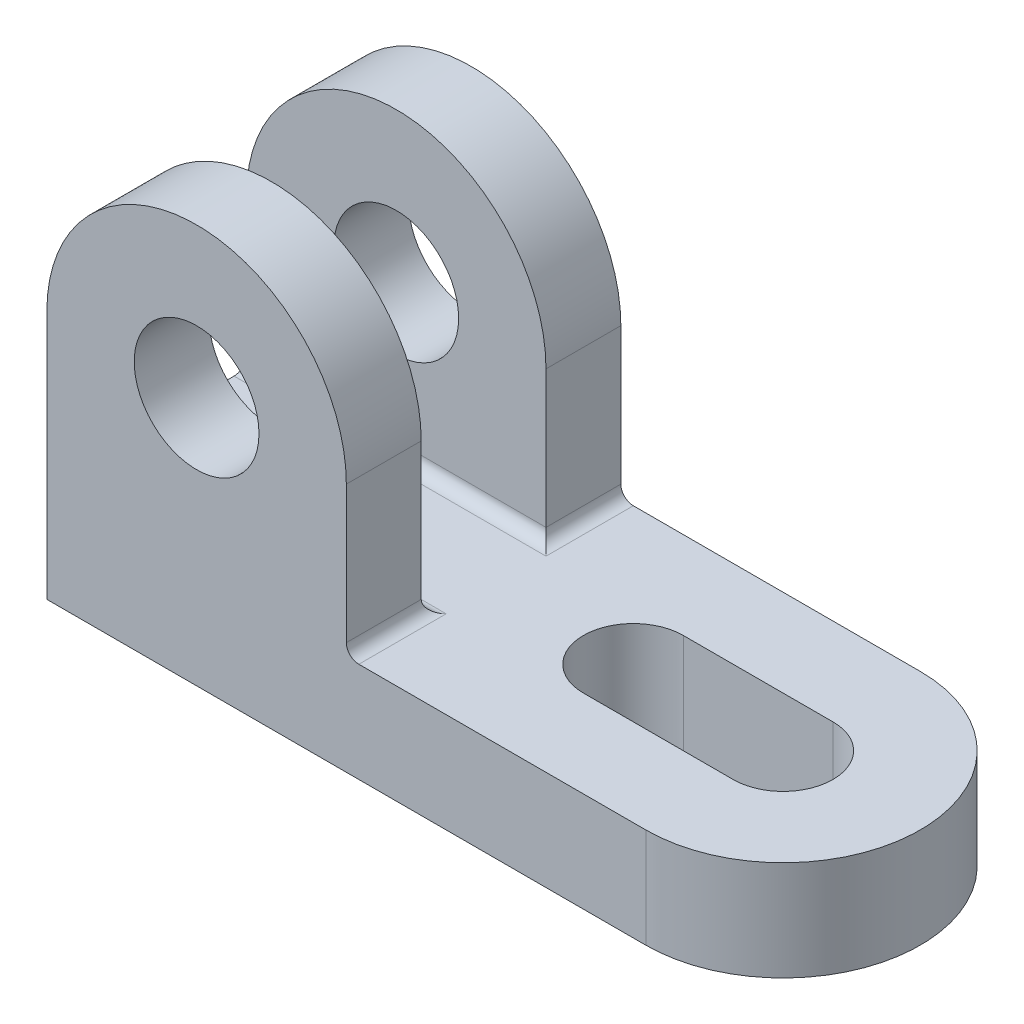
SolidWorks part; units mm, degrees
ref_plane "Ön Düzlem" through (0, 0, 0) normal (0, 0, 1) x (1, 0, 0)
ref_plane "Üst Düzlem" through (0, 0, 0) normal (0, 1, 0) x (1, 0, 0)
ref_plane "Sağ Düzlem" through (0, 0, 0) normal (1, 0, 0) x (0, 0, -1)
sketch "Sketch1" plane through (0, 0, 0) normal (0, 1, 0) x (1, 0, 0)
  line L1 (-59, -22) -> (59, -22)
  line L2 (-59, -22) -> (-59, 22)
  line L3 (-59, 22) -> (59, 22)
  line L4 (59, -22) -> (59, 22)
  line L5 (-59, -22) -> (59, 22) construction
  line L6 (-59, 22) -> (59, -22) construction
  circle A0 centre (37, 0) radius 22
  point P0 (0, 0)
  dimension "D1" = 118
  dimension "D2" = 44
extrude "Boss-Extrude1" add sketch "Sketch1" along normal blind 16 contours A0 L3 L2 L1 | A0
sketch "Sketch2" plane through (0, 16, 0) normal (0, 1, 0) x (1, 0, 0)
  line L0 (37, 0) -> (13, 0) construction
  line L1 (37, -8) -> (13, -8)
  line L2 (37, 8) -> (13, 8)
  arc A0 (37, -8) -> (37, 8) centre (37, 0) ccw
  arc A1 (13, 8) -> (13, -8) centre (13, 0) ccw
  point P4 (25, 0)
  dimension "D2" = 8
  dimension "D1" = 24
extrude "Cut-Extrude1" cut sketch "Sketch2" against normal blind 16
sketch "Sketch3" plane through (0, 0, 22) normal (0, 0, 1) x (1, 0, 0)
  line L0 (-59, 0) -> (37, 0) construction
  line L1 (-59, 16) -> (-11, 16)
  line L2 (-59, 16) -> (-59, 40)
  line L3 (-59, 40) -> (-11, 40)
  line L4 (-11, 16) -> (-11, 40)
  circle A0 centre (-35, 40) radius 24
  circle A1 centre (-35, 40) radius 10
  line M7 (37, 16) -> (-59, 16)
  dimension "D3" = 20
  dimension "D1" = 40
  dimension "D2" = 48
extrude "Boss-Extrude2" add sketch "Sketch3" against normal blind 12 contours A0 L2 L1 | A0 L4 M7 | A1 L3 A0 | A1 L3 A0
mirror "Mirror1" about plane through (0, 0, 0) normal (0, 0, 1) of "Boss-Extrude2"
fillet "Fillet1" radius 2 4 edges at (-11, 16, 16) (-35, 16, 10) (-11, 16, -16) (-35, 16, -10)
